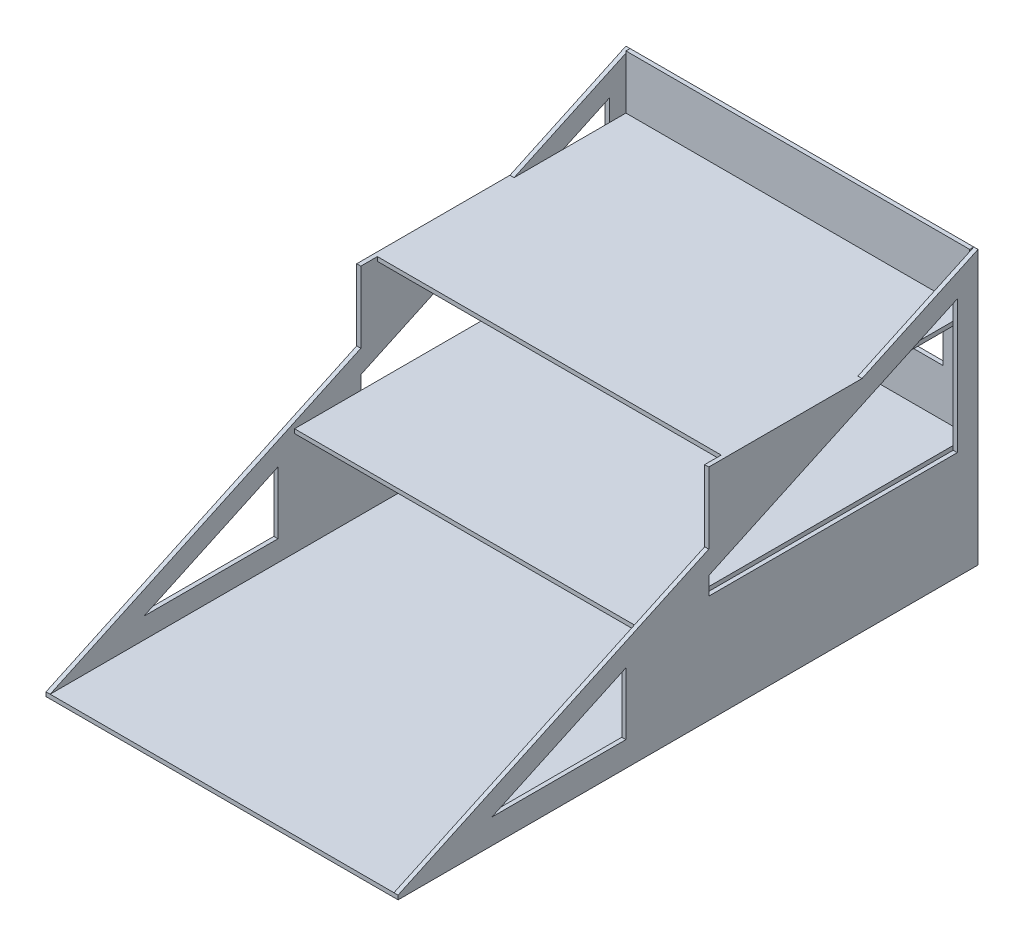
SolidWorks part; units mm, degrees
ref_plane "Front Plane" through (0, 0, 0) normal (0, 0, 1) x (1, 0, 0)
ref_plane "Top Plane" through (0, 0, 0) normal (0, 1, 0) x (1, 0, 0)
ref_plane "Right Plane" through (0, 0, 0) normal (1, 0, 0) x (0, 0, -1)
sketch "Sketch1" plane through (0, 0, 0) normal (0, 1, 0) x (1, 0, 0)
  line L1 (0, 0) -> (215.9, 0)
  line L2 (0, 0) -> (0, 355.6)
  line L3 (0, 355.6) -> (215.9, 355.6)
  line L4 (215.9, 0) -> (215.9, 355.6)
  dimension "D1" = 355.6
  dimension "D2" = 215.9
extrude "Boss-Extrude1" add sketch "Sketch1" along normal blind 2.54
sketch "Sketch2" plane through (215.9, 0, 0) normal (1, 0, 0) x (0, 0, -1)
  line L0 (355.6, 2.54) -> (355.6, 167.64)
  line L1 (355.6, 167.64) -> (0, 2.54)
  line L2 (0, 2.54) -> (355.6, 2.54)
  line L3 (139.7, 53.3986) -> (139.7, 15.24)
  line L4 (139.7, 15.24) -> (57.5121, 15.24)
  line L5 (57.5121, 15.24) -> (139.7, 53.3986)
  line L6 (342.9, 147.7415) -> (342.9, 66.04)
  line L7 (342.9, 66.04) -> (190.5, 66.04)
  line L8 (190.5, 76.9844) -> (342.9, 147.7415)
  line L9 (190.5, 66.04) -> (190.5, 76.9844)
  line L10 (355.6, 134.62) -> (190.5, 134.62)
  line L11 (190.5, 134.62) -> (190.5, 90.9864)
  line L12 (190.5, 90.9864) -> (284.48, 134.62)
  dimension "D1" = 165.1
  dimension "D2" = 12.7
  dimension "D3" = 12.7
  dimension "D4" = 12.7
  dimension "D5" = 12.7
  dimension "D6" = 63.5
  dimension "D7" = 50.8
  dimension "D8" = 215.9
  dimension "D9" = 33.02
  dimension "D10" = 165.1
extrude "Boss-Extrude2" add sketch "Sketch2" against normal blind 2.54 contours L2 L0 L1
sketch "Sketch3" plane through (215.9, 0, 0) normal (1, 0, 0) x (0, 0, -1)
  line L0 (139.7, 15.24) -> (57.5121, 15.24) construction
  line L1 (139.7, 53.3986) -> (139.7, 15.24) construction
  line L2 (57.5121, 15.24) -> (139.7, 53.3986) construction
  line L3 (190.5, 66.04) -> (190.5, 76.9844) construction
  line L4 (342.9, 66.04) -> (190.5, 66.04) construction
  line L5 (342.9, 147.7415) -> (342.9, 66.04) construction
  line L6 (190.5, 76.9844) -> (342.9, 147.7415) construction
  line L7 (139.7, 15.24) -> (57.5121, 15.24)
  line L8 (139.7, 53.3986) -> (139.7, 15.24)
  line L9 (57.5121, 15.24) -> (139.7, 53.3986)
  line L10 (190.5, 66.04) -> (190.5, 76.9844)
  line L11 (342.9, 66.04) -> (190.5, 66.04)
  line L12 (342.9, 147.7415) -> (342.9, 66.04)
  line L13 (190.5, 76.9844) -> (342.9, 147.7415)
extrude "Cut-Extrude4" cut sketch "Sketch3" against normal blind 2.54
sketch "Sketch5" plane through (0, 0, 0) normal (-1, 0, 0) x (0, 0, 1)
  line L3 (0, 2.54) -> (-355.6, 167.64)
  line L4 (-355.6, 167.64) -> (-355.6, 2.54)
  line L5 (-355.6, 2.54) -> (0, 2.54)
  line L6 (0, 2.54) -> (-355.6, 167.64)
  line L7 (-355.6, 167.64) -> (-355.6, 2.54)
  line L8 (-355.6, 2.54) -> (0, 2.54)
  dimension "D1" = 0
extrude "Boss-Extrude3" add sketch "Sketch5" against normal blind 2.54
sketch "Sketch6" plane through (0, 0, 0) normal (-1, 0, 0) x (0, 0, 1)
  line L0 (-139.7, 15.24) -> (-57.5121, 15.24) construction
  line L1 (-139.7, 53.3986) -> (-139.7, 15.24) construction
  line L2 (-57.5121, 15.24) -> (-139.7, 53.3986) construction
  line L3 (-342.9, 66.04) -> (-190.5, 66.04) construction
  line L4 (-342.9, 147.7415) -> (-342.9, 66.04) construction
  line L5 (-190.5, 66.04) -> (-190.5, 76.9844) construction
  line L6 (-190.5, 76.9844) -> (-342.9, 147.7415) construction
  line L7 (-139.7, 15.24) -> (-57.5121, 15.24)
  line L8 (-139.7, 53.3986) -> (-139.7, 15.24)
  line L9 (-57.5121, 15.24) -> (-139.7, 53.3986)
  line L10 (-342.9, 66.04) -> (-190.5, 66.04)
  line L11 (-342.9, 147.7415) -> (-342.9, 66.04)
  line L12 (-190.5, 66.04) -> (-190.5, 76.9844)
  line L13 (-190.5, 76.9844) -> (-342.9, 147.7415)
extrude "Cut-Extrude5" cut sketch "Sketch6" against normal blind 2.54
sketch "Sketch7" plane through (0, 0, -355.6) normal (0, 0, -1) x (-1, 0, 0)
  line L0 (-213.36, 167.64) -> (-2.54, 2.54) construction
  line L1 (-213.36, 2.54) -> (-2.54, 2.54)
  line L2 (-213.36, 2.54) -> (-213.36, 167.64)
  line L3 (-213.36, 167.64) -> (-2.54, 167.64)
  line L4 (-2.54, 2.54) -> (-2.54, 167.64)
  line L5 (-196.85, 15.24) -> (-19.05, 15.24)
  line L6 (-196.85, 15.24) -> (-196.85, 46.99)
  line L7 (-196.85, 46.99) -> (-19.05, 46.99)
  line L8 (-19.05, 15.24) -> (-19.05, 46.99)
  line L9 (-196.85, 97.79) -> (-19.05, 97.79)
  line L10 (-196.85, 97.79) -> (-196.85, 129.54)
  line L11 (-196.85, 129.54) -> (-19.05, 129.54)
  line L12 (-19.05, 97.79) -> (-19.05, 129.54)
  point P14 (-107.95, 129.54)
  point P15 (-107.95, 85.09)
  point P16 (-107.95, 46.99)
  dimension "D1" = 177.8
  dimension "D2" = 31.75
  dimension "D3" = 12.7
  dimension "D4" = 50.8
extrude "Boss-Extrude4" add sketch "Sketch7" against normal blind 2.54
sketch "Sketch8" plane through (0, 0, -353.06) normal (0, 0, 1) x (1, 0, 0)
  line L0 (2.54, 2.54) -> (2.54, 166.4607) construction
  line L1 (2.54, 68.58) -> (213.36, 68.58)
  line L2 (2.54, 68.58) -> (2.54, 66.04)
  line L3 (2.54, 66.04) -> (213.36, 66.04)
  line L4 (213.36, 68.58) -> (213.36, 66.04)
  line L5 (213.36, 166.4607) -> (213.36, 2.54) construction
  line L6 (213.36, 2.54) -> (2.54, 2.54) construction
  dimension "D1" = 2.54
  dimension "D2" = 63.5
extrude "Boss-Extrude6" add sketch "Sketch8" along normal blind 203.2 separate body
sketch "Sketch9" plane through (0, 0, -353.06) normal (0, 0, 1) x (1, 0, 0)
  line L0 (2.54, 2.54) -> (2.54, 166.4607) construction
  line L1 (2.54, 134.62) -> (213.36, 134.62)
  line L2 (2.54, 134.62) -> (2.54, 132.08)
  line L3 (2.54, 132.08) -> (213.36, 132.08)
  line L4 (213.36, 134.62) -> (213.36, 132.08)
  line L5 (213.36, 166.4607) -> (213.36, 2.54) construction
  line L6 (213.36, 68.58) -> (2.54, 68.58) construction
  dimension "D1" = 63.5
  dimension "D2" = 2.54
extrude "Boss-Extrude7" add sketch "Sketch9" along normal blind 152.4
sketch "Sketch10" plane through (215.9, 0, 0) normal (1, 0, 0) x (0, 0, -1)
  line L0 (190.5, 134.62) -> (190.5, 90.9864) construction
  line L1 (355.6, 134.62) -> (190.5, 134.62) construction
  line L2 (190.5, 134.62) -> (190.5, 90.9864)
  line L3 (355.6, 134.62) -> (190.5, 134.62)
  line L4 (190.5, 90.9864) -> (284.48, 134.62)
  line M10 (355.6, 167.64) -> (0, 2.54)
extrude "Boss-Extrude8" add sketch "Sketch10" against normal up to vertex contours L3 L2 M10
sketch "Sketch11" plane through (0, 0, 0) normal (-1, 0, 0) x (0, 0, 1)
  line L0 (-355.6, 134.62) -> (-190.5, 134.62) construction
  line L1 (-190.5, 134.62) -> (-190.5, 90.9864) construction
  line L2 (-355.6, 134.62) -> (-190.5, 134.62)
  line L3 (-190.5, 134.62) -> (-190.5, 90.9864)
  line L4 (-284.48, 134.62) -> (-190.5, 90.9864)
  line M10 (0, 2.54) -> (-355.6, 167.64)
extrude "Boss-Extrude9" add sketch "Sketch11" against normal up to vertex contours L3 L2 M10
equation "\"D3@Sketch2\"=\"D2@Sketch2\""
equation "\"D4@Sketch2\"=\"D2@Sketch2\""
equation "\"D5@Sketch2\"=\"D2@Sketch2\""
